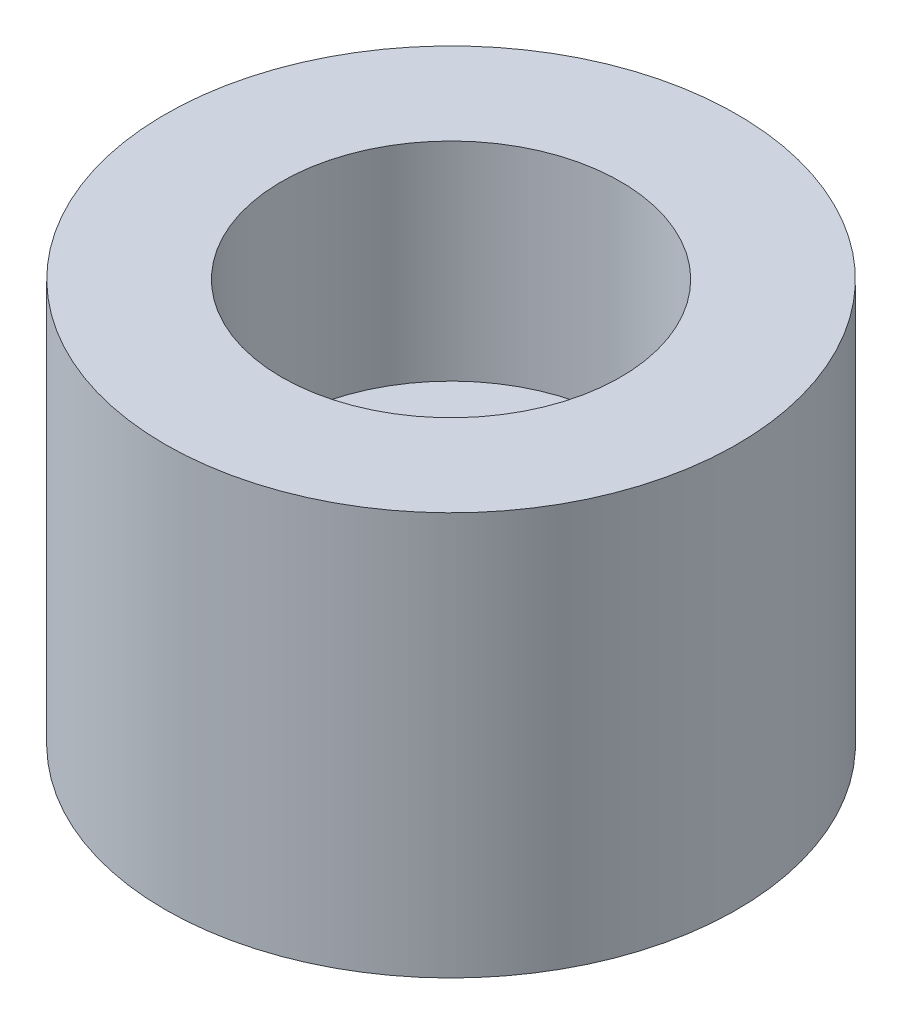
SolidWorks part; units mm, degrees
ref_plane "Front Plane" through (0, 0, 0) normal (0, 0, 1) x (1, 0, 0)
ref_plane "Top Plane" through (0, 0, 0) normal (0, 1, 0) x (1, 0, 0)
ref_plane "Right Plane" through (0, 0, 0) normal (1, 0, 0) x (0, 0, -1)
sketch "Sketch1" plane through (0, 0, 0) normal (0, 1, 0) x (1, 0, 0)
  circle A0 centre (0, 0) radius 27.5
  circle A1 centre (0, 0) radius 23.9
  dimension "D1" = 55
  dimension "D2" = 47.8
extrude "Boss-Extrude1" add sketch "Sketch1" along normal blind 10.75
sketch "Sketch2" plane through (0, 10.75, 0) normal (0, 1, 0) x (1, 0, 0)
  circle A2 centre (0, 0) radius 27.5
  circle A3 centre (0, 0) radius 21.5
  dimension "D1" = 55
  dimension "D2" = 6
extrude "Boss-Extrude2" add sketch "Sketch2" along normal blind 3
sketch "Sketch3" plane through (0, 13.75, 0) normal (0, 1, 0) x (1, 0, 0)
  circle A0 centre (0, 0) radius 27.5
  dimension "D1" = 55
extrude "Boss-Extrude3" add sketch "Sketch3" along normal blind 5
sketch "Sketch4" plane through (0, 18.75, 0) normal (0, 1, 0) x (1, 0, 0)
  circle A0 centre (0, 0) radius 16.3
  circle A1 centre (0, 0) radius 27.5
  dimension "D1" = 32.6
  dimension "D2" = 55
extrude "Boss-Extrude4" add sketch "Sketch4" along normal blind 20
